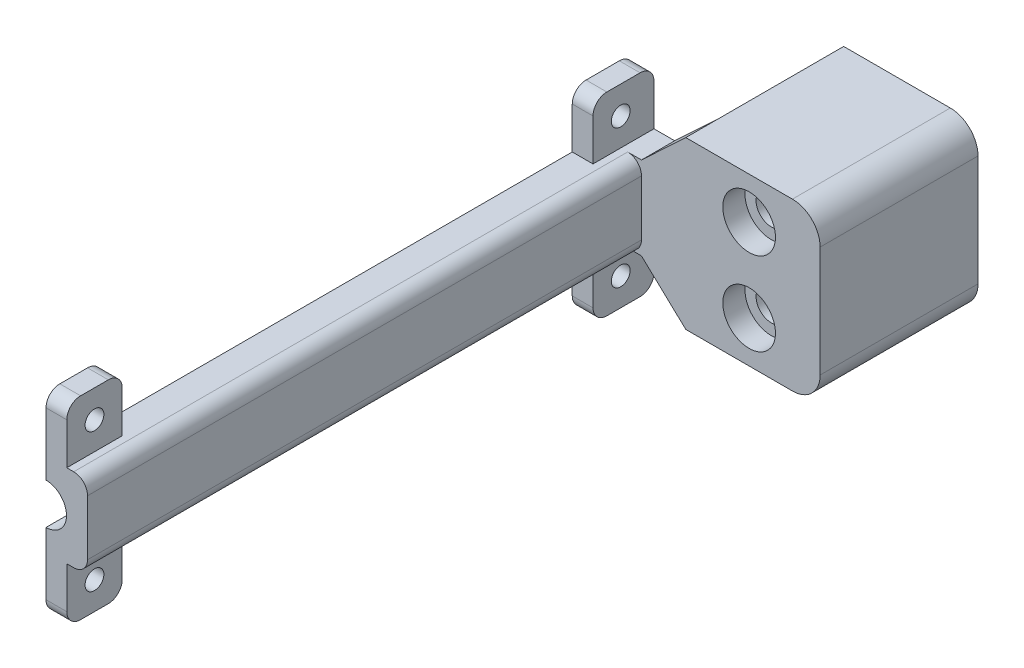
SolidWorks part; units mm, degrees
ref_plane "Front Plane" through (0, 0, 0) normal (0, 0, 1) x (1, 0, 0)
ref_plane "Top Plane" through (0, 0, 0) normal (0, 1, 0) x (1, 0, 0)
ref_plane "Right Plane" through (0, 0, 0) normal (1, 0, 0) x (0, 0, -1)
sketch "Sketch2" plane through (0, 0, 0) normal (0, 0, 1) x (1, 0, 0)
  line L7 (42.5, -2.5) -> (42.5, 17.5)
  line L8 (37.5, 22.5) -> (14, 22.5)
  line L9 (-56.3215, 29.5) -> (-88, 29.5)
  line L10 (-93, 24.5) -> (-93, 13.5)
  line L11 (-93, 13.5) -> (-93, 2.5)
  line L12 (-88, -2.5) -> (-63.2649, -2.5)
  line L13 (14, -7.5) -> (37.5, -7.5)
  line L14 (42.5, -2.5) -> (42.5, 17.5)
  line L15 (37.5, 22.5) -> (18.253, 22.5)
  line L16 (-56.3215, 29.5) -> (-88, 29.5)
  line L17 (-93, 24.5) -> (-93, 13.5)
  line L18 (-93, 13.5) -> (-93, 2.5)
  line L19 (-88, -2.5) -> (-63.2649, -2.5)
  line L20 (18.253, -7.5) -> (37.5, -7.5)
  arc A0 (-57.3436, 29.5) -> (-62.5959, -2.545) centre (-23.5, 7.5) ccw
  arc A1 (-62.0268, 29.5) -> (-66.724, -2.5) centre (-23.5, 7.5) ccw
  circle A2 centre (-23.5, 7.5) radius 44.3657 construction
  circle A3 centre (-23.5, 7.5) radius 40.3657 construction
  arc A4 (18.253, -7.5) -> (18.253, 22.5) centre (-23.5, 7.5) ccw
  circle A5 centre (29.6829, 15) radius 2.75 construction
  circle A6 centre (29.6829, 15) radius 2.75
  circle A7 centre (29.6829, 0) radius 2.75 construction
  circle A8 centre (29.6829, 0) radius 2.75
  arc A12 (42.5, 17.5) -> (37.5, 22.5) centre (37.5, 17.5) ccw
  arc A13 (9.5882, 25.1471) -> (14, 22.5) centre (14, 27.5) ccw
  arc A14 (9.5882, 25.1471) -> (-52.4601, 31.3235) centre (-23.5, 7.5) ccw
  arc A15 (-56.3215, 29.5) -> (-52.4601, 31.3235) centre (-56.3215, 34.5) ccw
  arc A16 (-88, 29.5) -> (-93, 24.5) centre (-88, 24.5) ccw
  arc A17 (-93, 2.5) -> (-88, -2.5) centre (-88, 2.5) ccw
  arc A18 (-58.5867, -5.7353) -> (-63.2649, -2.5) centre (-63.2649, -7.5) ccw
  arc A19 (-58.5867, -5.7353) -> (9.5882, -10.1471) centre (-23.5, 7.5) ccw
  arc A20 (14, -7.5) -> (9.5882, -10.1471) centre (14, -12.5) ccw
  arc A21 (37.5, -7.5) -> (42.5, -2.5) centre (37.5, -2.5) ccw
  arc A22 (42.5, 17.5) -> (37.5, 22.5) centre (37.5, 17.5) ccw
  arc A23 (13.9752, 22.5001) -> (14, 22.5) centre (14, 27.5) ccw
  arc A25 (-56.3215, 29.5) -> (-52.4601, 31.3235) centre (-56.3215, 34.5) ccw
  arc A26 (-88, 29.5) -> (-93, 24.5) centre (-88, 24.5) ccw
  arc A27 (-93, 2.5) -> (-88, -2.5) centre (-88, 2.5) ccw
  arc A28 (-58.5867, -5.7353) -> (-63.2649, -2.5) centre (-63.2649, -7.5) ccw
  arc A31 (37.5, -7.5) -> (42.5, -2.5) centre (37.5, -2.5) ccw
  circle M23 centre (29.6829, 15) radius 2.75
  circle M24 centre (29.6829, 0) radius 2.75
  line M33 (42.5, -2.5) -> (42.5, 17.5)
  arc M34 (42.5, 17.5) -> (37.5, 22.5) centre (37.5, 17.5) ccw
  line M35 (37.5, 22.5) -> (14, 22.5)
  line M48 (14, -7.5) -> (37.5, -7.5)
  arc M49 (37.5, -7.5) -> (42.5, -2.5) centre (37.5, -2.5) ccw
  dimension "D1" = 4
  dimension "D2" = 0
extrude "Boss-Extrude1" add sketch "Sketch2" along normal up to surface (21.5 mm away) contours A4 M48 M49 M33 M34 M35 M24 M23
sketch "Sketch3" plane through (0, 0, 21.5) normal (0, 0, 1) x (1, 0, 0)
  line L3 (18.253, -7.5) -> (37.5, -7.5)
  line L4 (42.5, -2.5) -> (42.5, 17.5)
  line L5 (37.5, 22.5) -> (18.253, 22.5)
  line L6 (18.253, -7.5) -> (37.5, -7.5)
  line L7 (42.5, -2.5) -> (42.5, 17.5)
  line L8 (37.5, 22.5) -> (18.253, 22.5)
  circle A0 centre (29.6829, 0) radius 2.75 construction
  circle A1 centre (29.6829, 15) radius 2.75 construction
  circle A2 centre (29.6829, 0) radius 2.75
  arc A3 (18.253, -7.5) -> (18.253, 22.5) centre (-23.5, 7.5) ccw
  arc A4 (37.5, -7.5) -> (42.5, -2.5) centre (37.5, -2.5) ccw
  arc A5 (42.5, 17.5) -> (37.5, 22.5) centre (37.5, 17.5) ccw
  arc A6 (18.253, -7.5) -> (18.253, 22.5) centre (-23.5, 7.5) ccw
  arc A7 (37.5, -7.5) -> (42.5, -2.5) centre (37.5, -2.5) ccw
  arc A8 (42.5, 17.5) -> (37.5, 22.5) centre (37.5, 17.5) ccw
  circle A9 centre (29.6829, 15) radius 2.75
  dimension "D1" = 0
extrude "Boss-Extrude2" add sketch "Sketch3" along normal blind 2
sketch "Sketch4" plane through (0, 0, 23.5) normal (0, 0, 1) x (1, 0, 0)
  line L0 (10.25, 15) -> (18.253, 22.5)
  line L1 (-4.75, 0) -> (10.25, 0)
  line L2 (-4.75, 0) -> (-4.75, 15)
  line L3 (-4.75, 15) -> (10.25, 15)
  line L4 (10.25, 0) -> (10.25, 15)
  line L5 (-4.75, 0) -> (10.25, 15) construction
  line L6 (-4.75, 15) -> (10.25, 0) construction
  line L7 (10.25, 0) -> (18.253, -7.5)
  line L9 (18.253, -7.5) -> (37.5, -7.5)
  line L10 (42.5, -2.5) -> (42.5, 17.5)
  line L11 (37.5, 22.5) -> (18.253, 22.5)
  line L12 (18.253, -7.5) -> (37.5, -7.5)
  line L13 (42.5, -2.5) -> (42.5, 17.5)
  line L14 (37.5, 22.5) -> (18.253, 22.5)
  circle A0 centre (2.75, 7.5) radius 3.7
  circle A1 centre (29.6829, 0) radius 2.75 construction
  circle A2 centre (29.6829, 15) radius 2.75 construction
  circle A3 centre (29.6829, 0) radius 2.75
  arc A4 (18.253, -7.5) -> (18.253, 22.5) centre (-23.5, 7.5) ccw
  arc A5 (37.5, -7.5) -> (42.5, -2.5) centre (37.5, -2.5) ccw
  arc A6 (42.5, 17.5) -> (37.5, 22.5) centre (37.5, 17.5) ccw
  arc A7 (18.253, -7.5) -> (18.253, 22.5) centre (-23.5, 7.5) ccw
  arc A8 (37.5, -7.5) -> (42.5, -2.5) centre (37.5, -2.5) ccw
  arc A9 (42.5, 17.5) -> (37.5, 22.5) centre (37.5, 17.5) ccw
  circle A10 centre (29.6829, 15) radius 2.75
  circle M11 centre (29.6829, 0) radius 2.75
  arc M12 (18.253, 22.5) -> (18.253, -7.5) centre (-23.5, 7.5) cw
  line M13 (18.253, -7.5) -> (37.5, -7.5)
  arc M14 (37.5, -7.5) -> (42.5, -2.5) centre (37.5, -2.5) ccw
  line M15 (42.5, -2.5) -> (42.5, 17.5)
  arc M16 (42.5, 17.5) -> (37.5, 22.5) centre (37.5, 17.5) ccw
  line M17 (37.5, 22.5) -> (18.253, 22.5)
  circle M18 centre (29.6829, 15) radius 2.75
  dimension "D1" = 15
  dimension "D2" = 15
  dimension "D3" = 0
extrude "Boss-Extrude3" add sketch "Sketch4" along normal blind 5 contours L4 L7 L0 M12 | L1 L4 L3 L2 A0 | M17 M12 M13 M14 M15 M16 M18 M11
sketch "Sketch5" plane through (0, 0, 28.5) normal (0, 0, 1) x (1, 0, 0)
  line L1 (-4.75, 0) -> (10.25, 0)
  line L2 (-4.75, 0) -> (-4.75, 15)
  line L3 (-4.75, 15) -> (10.25, 15)
  line L4 (10.25, 0) -> (10.25, 15)
  line L5 (-4.75, 0) -> (10.25, 15) construction
  line L6 (-4.75, 15) -> (10.25, 0) construction
  circle A0 centre (2.75, 7.5) radius 3.7 construction
  circle A1 centre (2.75, 7.5) radius 3.7
extrude "Boss-Extrude4" add sketch "Sketch5" along normal blind 100
sketch "Sketch6" plane through (0, 0, 128.5) normal (0, 0, 1) x (1, 0, 0)
  line L0 (2.75, 7.5) -> (2.75, 15)
  line L1 (10.25, 15) -> (-4.75, 15) construction
  line L2 (2.75, 15) -> (2.75, 0)
  line L3 (-4.75, 0) -> (10.25, 0) construction
  line L8 (10.25, 0) -> (10.25, 15)
  line L9 (10.25, 15) -> (-4.75, 15)
  line L10 (-4.75, 15) -> (-4.75, 0)
  line L11 (-4.75, 0) -> (10.25, 0)
  line L12 (10.25, 0) -> (10.25, 15)
  line L13 (10.25, 15) -> (-4.75, 15)
  line L14 (-4.75, 15) -> (-4.75, 0)
  line L15 (-4.75, 0) -> (10.25, 0)
  line M6 (10.25, 15) -> (-4.75, 15)
  line M7 (-4.75, 15) -> (-4.75, 0)
  line M8 (-4.75, 0) -> (10.25, 0)
  circle M9 centre (2.75, 7.5) radius 3.7
  dimension "D1" = 0
extrude "Cut-Extrude1" cut sketch "Sketch6" against normal through all both and the other way through all contours L2 L0 M9 M6 M7 M8
sketch "Sketch7" plane through (0, 0, 0) normal (0, -1, 0) x (1, 0, 0)
  line L0 (2.75, 23.5) -> (2.75, 128.5) construction
  line L1 (10.25, 128.5) -> (2.75, 128.5)
  line L2 (10.25, 128.5) -> (10.25, 118.5)
  line L3 (10.25, 118.5) -> (2.75, 118.5)
  line L4 (2.75, 128.5) -> (2.75, 118.5)
  line L5 (10.25, 128.5) -> (10.25, 28.5) construction
  line L6 (2.75, 23.5) -> (10.25, 23.5)
  line L7 (2.75, 23.5) -> (2.75, 33.5)
  line L8 (2.75, 33.5) -> (10.25, 33.5)
  line L9 (10.25, 23.5) -> (10.25, 33.5)
  line L10 (6.5, 23.5) -> (6.5, 128.5)
  line M3 (2.75, 128.5) -> (2.75, 23.5)
  line M4 (2.75, 23.5) -> (10.25, 23.5)
  dimension "D1" = 10
  dimension "D2" = 10
extrude "Boss-Extrude5" add sketch "Sketch7" along normal blind 10 contours L3 L10 L1 M3 | L10 L8 M4 M3
sketch "Sketch8" plane through (0, 15, 0) normal (0, 1, 0) x (1, 0, 0)
  line L4 (6.5, -118.5) -> (2.75, -118.5)
  line L5 (6.5, -128.5) -> (6.5, -118.5)
  line L6 (2.75, -128.5) -> (6.5, -128.5)
  line L7 (2.75, -118.5) -> (2.75, -128.5)
  line L8 (6.5, -118.5) -> (2.75, -118.5)
  line L9 (6.5, -128.5) -> (6.5, -118.5)
  line L10 (2.75, -128.5) -> (6.5, -128.5)
  line L11 (2.75, -118.5) -> (2.75, -128.5)
  line L12 (6.5, -23.5) -> (2.75, -23.5)
  line L13 (6.5, -33.5) -> (6.5, -23.5)
  line L14 (2.75, -33.5) -> (6.5, -33.5)
  line L15 (2.75, -23.5) -> (2.75, -33.5)
  line L16 (6.5, -23.5) -> (2.75, -23.5)
  line L17 (6.5, -33.5) -> (6.5, -23.5)
  line L18 (2.75, -33.5) -> (6.5, -33.5)
  line L19 (2.75, -23.5) -> (2.75, -33.5)
  dimension "D1" = 0
  dimension "D2" = 0
extrude "Boss-Extrude6" add sketch "Sketch8" along normal blind 10
sketch "Sketch9" plane through (2.75, 0, 0) normal (-1, 0, 0) x (0, 0, 1)
  line L0 (118.5, 15) -> (128.5, 25) construction
  line L1 (128.5, -10) -> (118.5, 0) construction
  line L2 (76, 0) -> (76, -10) construction
  line L3 (33.5, 0) -> (118.5, 0) construction
  line L4 (23.5, -10) -> (33.5, 0) construction
  line L5 (33.5, 15) -> (23.5, 25) construction
  circle A0 centre (123.5, -5) radius 1.7
  circle A1 centre (123.5, 20) radius 1.7
  circle A2 centre (28.5, 20) radius 1.7
  circle A3 centre (28.5, -5) radius 1.7
  dimension "D1" = 3.4
  dimension "D2" = 3.4
extrude "Cut-Extrude2" cut sketch "Sketch9" against normal blind 5 and the other way through all
sketch "Sketch10" plane through (0, 0, 23.5) normal (0, 0, -1) x (-1, 0, 0)
  line L10 (-2.75, -10) -> (-2.75, 3.8)
  line L11 (-2.75, 11.2) -> (-2.75, 25)
  line L12 (-2.75, 25) -> (-6.5, 25)
  line L13 (-6.5, 25) -> (-6.5, 15)
  line L14 (-6.5, 15) -> (-10.25, 15)
  line L15 (-10.25, 15) -> (-18.253, 22.5)
  line L16 (-18.253, -7.5) -> (-10.25, 0)
  line L17 (-10.25, 0) -> (-6.5, 0)
  line L18 (-6.5, 0) -> (-6.5, -10)
  line L19 (-6.5, -10) -> (-2.75, -10)
  line L20 (-2.75, -10) -> (-2.75, 3.8)
  line L21 (-2.75, 11.2) -> (-2.75, 25)
  line L22 (-2.75, 25) -> (-6.5, 25)
  line L23 (-6.5, 25) -> (-6.5, 15)
  line L24 (-6.5, 15) -> (-10.25, 15)
  line L25 (-10.25, 15) -> (-18.253, 22.5)
  line L26 (-18.253, -7.5) -> (-10.25, 0)
  line L27 (-10.25, 0) -> (-6.5, 0)
  line L28 (-6.5, 0) -> (-6.5, -10)
  line L29 (-6.5, -10) -> (-2.75, -10)
  arc A2 (-2.75, 11.2) -> (-2.75, 3.8) centre (-2.75, 7.5) ccw
  arc A3 (-18.253, 22.5) -> (-18.253, -7.5) centre (23.5, 7.5) ccw
  arc A4 (-2.75, 11.2) -> (-2.75, 3.8) centre (-2.75, 7.5) ccw
  arc A5 (-18.253, 22.5) -> (-18.253, -7.5) centre (23.5, 7.5) ccw
  dimension "D1" = 0
extrude "Boss-Extrude7" add sketch "Sketch10" along normal blind 1
fillet "Fillet1" radius 2.5 10 edges at (4.625, -10, 22.5) (4.625, -10, 33.5) (4.625, 25, 22.5) (4.625, 25, 33.5) (4.625, 25, 118.5) (4.625, 25, 128.5) (4.625, -10, 118.5) (4.625, -10, 128.5) (10.25, 0, 78.5) (10.25, 15, 78.5)
sketch "Sketch11" plane through (0, 0, 28.5) normal (0, 0, 1) x (1, 0, 0)
  circle A1 centre (29.6829, 15) radius 4.75
  circle A2 centre (29.6829, 0) radius 4.75
  dimension "D1" = 9.5
  dimension "D2" = 9.5
extrude "Cut-Extrude3" cut sketch "Sketch11" against normal blind 4
